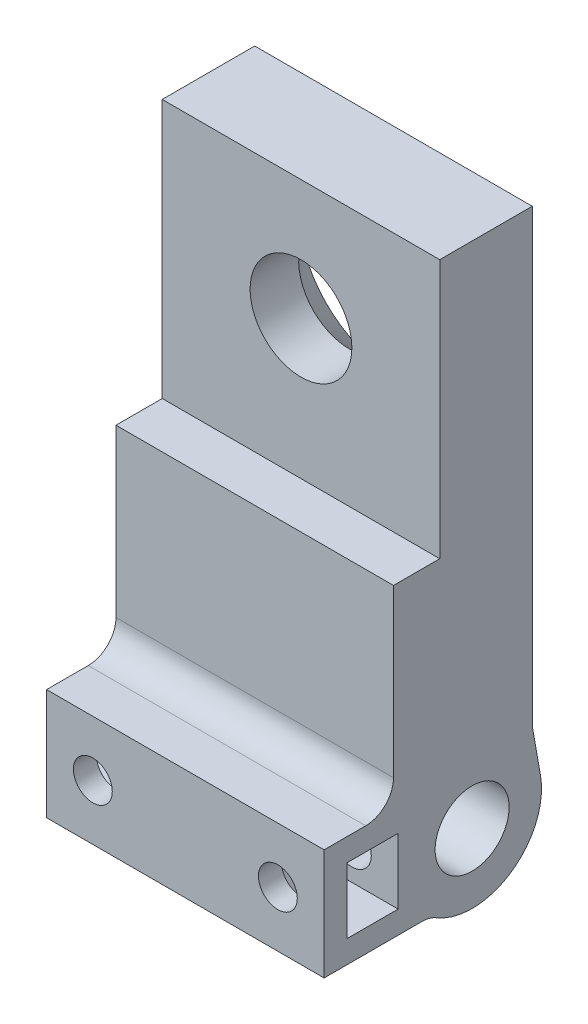
SolidWorks part; units mm, degrees
material "3D printed plastic"
ref_plane "Front Plane" through (0, 0, 0) normal (0, 0, 1) x (1, 0, 0)
ref_plane "Top Plane" through (0, 0, 0) normal (0, 1, 0) x (1, 0, 0)
ref_plane "Right Plane" through (0, 0, 0) normal (1, 0, 0) x (0, 0, -1)
sketch "Sketch1" plane through (0, 0, 0) normal (1, 0, 0) x (0, 0, -1)
  line L0 (6.5, 55) -> (6.5, 6.3274)
  line L1 (6.5, 6.3274) -> (7.3861, 1.3024)
  line L2 (-7.3861, -1.3024) -> (-8.5, 5.0151)
  line L3 (-8.5, 5.0151) -> (-8.5, 55)
  line L4 (-8.5, 55) -> (6.5, 55)
  circle A0 centre (0, 0) radius 4
  arc A1 (7.3861, 1.3024) -> (-7.3861, -1.3024) centre (0, 0) cw
  dimension "D1" = 8
  dimension "D2" = 6.5
  dimension "D3" = 15
  dimension "D4" = 15
  dimension "D5" = 10
  dimension "D6" = 55
extrude "Boss-Extrude1" add sketch "Sketch1" along normal mid plane 30
sketch "Sketch2" plane through (15, 0, 0) normal (1, 0, 0) x (0, 0, -1)
  line L1 (-4.5, 6) -> (-16, 6)
  line L2 (-4.5, 6) -> (-4.5, -6)
  line L3 (-4.5, -6) -> (-16, -6)
  line L4 (-16, 6) -> (-16, -6)
  arc A0 (-7.3861, -1.3024) -> (7.3861, 1.3024) centre (0, 0) ccw construction
  circle A1 centre (0, 0) radius 4 construction
  dimension "D2" = 16
  dimension "D1" = 12
extrude "Boss-Extrude2" add sketch "Sketch2" against normal up to surface (30 mm away) up to face at (-15, 18.9928, 0.4496)
fillet "Fillet1" radius 3 3 edges at (0, -6, 4.5) (0, 6.3274, -6.5) (0, 6, 8.5)
sketch "Sketch3" plane through (0, 0, 8.5) normal (0, 0, 1) x (1, 0, 0)
  line L0 (0, 42) -> (0, 0) construction
  circle A0 centre (0, 42) radius 2.1
  dimension "D1" = 42
  dimension "D2" = 4.2
extrude "Cut-Extrude1" cut sketch "Sketch3" against normal through all
sketch "Sketch4" plane through (0, 0, 16) normal (0, 0, 1) x (1, 0, 0)
  line L0 (10, 0) -> (-10, 0) construction
  line L1 (-15, 6) -> (-15, -6) construction
  circle A0 centre (-10, 0) radius 2.1
  circle A1 centre (10, 0) radius 2.1
  dimension "D1" = 4.2
  dimension "D2" = 5
extrude "Cut-Extrude2" cut sketch "Sketch4" against normal up to next
sketch "Sketch5" plane through (0, 0, 16) normal (0, 0, 1) x (1, 0, 0)
  line L0 (-12.0496, 3.55) -> (-15, 3.55)
  line L1 (-14.0992, 0) -> (-12.0496, -3.55) construction
  line L2 (-12.0496, -3.55) -> (-7.9504, -3.55)
  line L3 (-7.9504, -3.55) -> (-5.9008, 0)
  line L4 (-5.9008, 0) -> (-7.9504, 3.55)
  line L5 (-7.9504, 3.55) -> (-12.0496, 3.55)
  line L6 (-12.0496, 3.55) -> (-14.0992, 0) construction
  line L7 (-15, 6) -> (-15, -6) construction
  line L8 (-15, 3.55) -> (-15, -3.55)
  line L9 (-15, -3.55) -> (-12.0496, -3.55)
  circle A0 centre (-10, 0) radius 3.55 construction
  dimension "D1" = 7.1
extrude "Cut-Extrude3" cut sketch "Sketch5" against normal blind 5.5 from offset 2.5 offset against normal yes
mirror "Mirror1" about plane through (0, 0, 0) normal (1, 0, 0) of "Cut-Extrude3"
sketch "Sketch6" plane through (0, 0, -6.5) normal (0, 0, -1) x (-1, 0, 0)
  line L0 (-15, 1.3024) -> (-15, 6.069) construction
  circle A0 centre (-7, 18.75) radius 5
  circle A1 centre (0, 42) radius 2.1 construction
  dimension "D1" = 23.25
  dimension "D2" = 10
  dimension "D3" = 8
extrude "Cut-Extrude4" cut sketch "Sketch6" along normal through all and the other way blind 5
hole_wizard "CSK for M10 Hex Socket Countersunk Head Screw1" positions "Sketch8" profile "Sketch7" countersink size "M10" standard "DIN" end condition through all
sketch "Sketch8" plane through (0, 0, -6.5) normal (0, 0, -1) x (-1, 0, 0)
  point P0 (0, 42)
sketch "Sketch7" plane through (0, 42, -6.5) normal (1, 0, 0) x (0, 1, 0)
  line L0 (0, 0) -> (0, 22.5)
  line L1 (0, 22.5) -> (5.5, 22.5)
  line L2 (5.5, 22.5) -> (5.5, 4.75)
  line L3 (5.5, 4.75) -> (10.25, 0)
  line L5 (10.25, 0) -> (0, 0)
  line L6 (-5.5, 4.75) -> (-10.25, 0) construction
  line L11 (0, -6.35) -> (0, 107.95) construction
  dimension "Thru Hole Dia." = 11
  dimension "Thru Hole Depth" = 22.5
  dimension "Near C'Sink Dia." = 20.5
  dimension "Near C'Sink Angle" = 90
sketch "Sketch9" plane through (0, 0, 8.5) normal (0, 0, 1) x (1, 0, 0)
  line L0 (15, 55) -> (15, 9) construction
  line L1 (-15, 55) -> (15, 55)
  line L2 (-15, 55) -> (-15, 27)
  line L3 (-15, 27) -> (15, 27)
  line L4 (15, 55) -> (15, 27)
  circle A0 centre (0, 42) radius 5.5 construction
  dimension "D1" = 15
extrude "Cut-Extrude5" cut sketch "Sketch9" against normal blind 5
